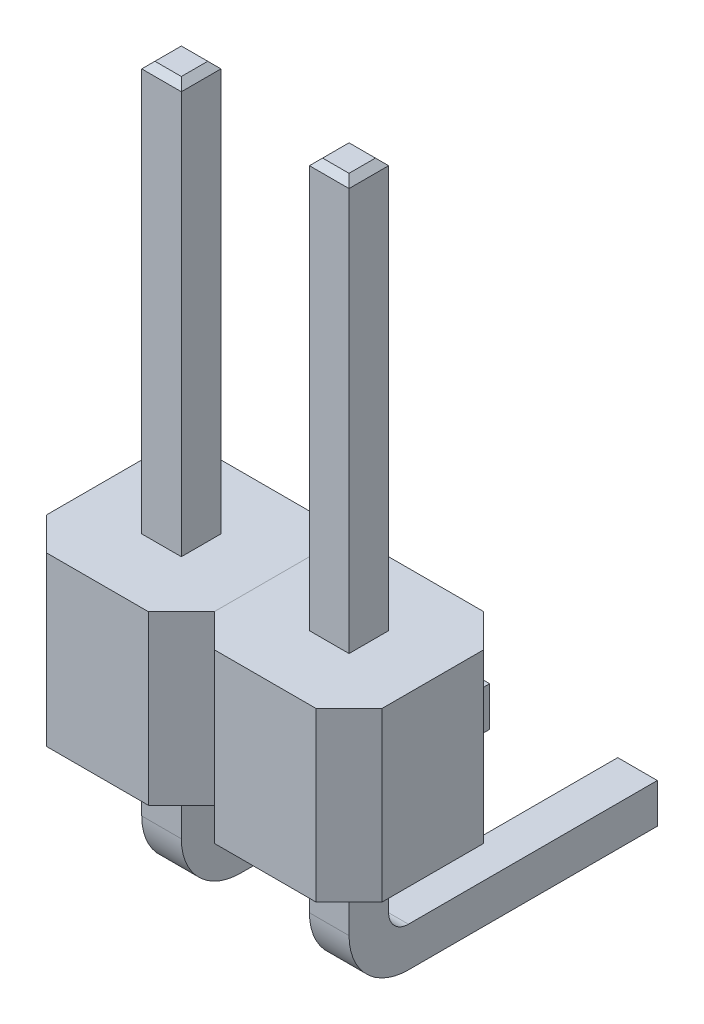
SolidWorks part; units mm, degrees
ref_plane "Front Plane" through (0, 0, 0) normal (0, 0, 1) x (1, 0, 0)
ref_plane "Top Plane" through (0, 0, 0) normal (0, 1, 0) x (1, 0, 0)
ref_plane "Right Plane" through (0, 0, 0) normal (1, 0, 0) x (0, 0, -1)
sketch "Sketch2" plane through (0, 0, 0) normal (1, 0, 0) x (0, -1, 0)
  line L0 (0.3, 3.2) -> (-0.3, 3.2)
  line L9 (-0.6, -1.27) -> (-10.5, -1.27) construction
  line L10 (0, 3.2) -> (0, -0.67) construction
  line L11 (-10.5, -1.57) -> (-10.5, -0.97)
  line L13 (-0.6, -0.97) -> (-10.5, -0.97)
  line L14 (-0.3, 3.2) -> (-0.3, -0.67)
  line L15 (-0.6, -1.57) -> (-10.5, -1.57)
  line L16 (0.3, 3.2) -> (0.3, -0.67)
  arc A3 (0, -0.67) -> (-0.6, -1.27) centre (-0.6, -0.67) cw construction
  arc A4 (-0.3, -0.67) -> (-0.6, -0.97) centre (-0.6, -0.67) cw
  arc A5 (0.3, -0.67) -> (-0.6, -1.57) centre (-0.6, -0.67) cw
  point P0 (-4.3, -1.27)
  point P1 (-0.6, -0.97)
  point P2 (0, 0)
  dimension "D1" = 0.6
  dimension "D4" = 6.2
  dimension "D5" = 3.2
  dimension "D6" = 10.8
  dimension "D7" = 1.27
  dimension "D8" = 0.6
  dimension "D2" = 0.3
  dimension "D3" = 0.3
extrude "Contact" add sketch "Sketch2" along normal mid plane 0.6
chamfer "Chamfer1" distance 0.1 angle 45 8 edges at (0, -0.3, -3.2) (0.3, 0, -3.2) (0, 0.3, -3.2) (-0.3, 0, -3.2) (0, 10.5, 0.97) (0.3, 10.5, 1.27) (0, 10.5, 1.57) (-0.3, 10.5, 1.27)
ref_plane "Плоскость1" through (0, 4.3, 0) normal (0, 1, 0) x (1, 0, 0)
sketch "Sketch1" plane through (0, 4.3, 0) normal (0, 1, 0) x (0, 0, -1)
  line L0 (0, 0) -> (-1.27, 0) construction
  line L5 (-1.27, 0) -> (-1.27, 1.27) construction
  line L6 (-2.04, 1.27) -> (-0.5, 1.27)
  line L7 (-0.5, 1.27) -> (0, 0.77)
  line L8 (0, 0.77) -> (0, -0.77)
  line L9 (-2.54, 0.77) -> (-2.54, -0.77)
  line L10 (-2.04, 1.27) -> (-2.54, 0.77)
  line L11 (-0.5, -1.27) -> (0, -0.77)
  line L12 (-2.04, -1.27) -> (-0.5, -1.27)
  line L13 (-2.04, -1.27) -> (-2.54, -0.77)
  point P13 (-2.54, 0)
  dimension "D1" = 1.27
  dimension "D2" = 45
  dimension "D3" = 0.5
extrude "Plastic" add sketch "Sketch1" against normal blind 2.54
pattern_linear "Линейный массив2" count 2 spacing 2.54 along (1, 0, 0) of "Plastic", "Contact"
